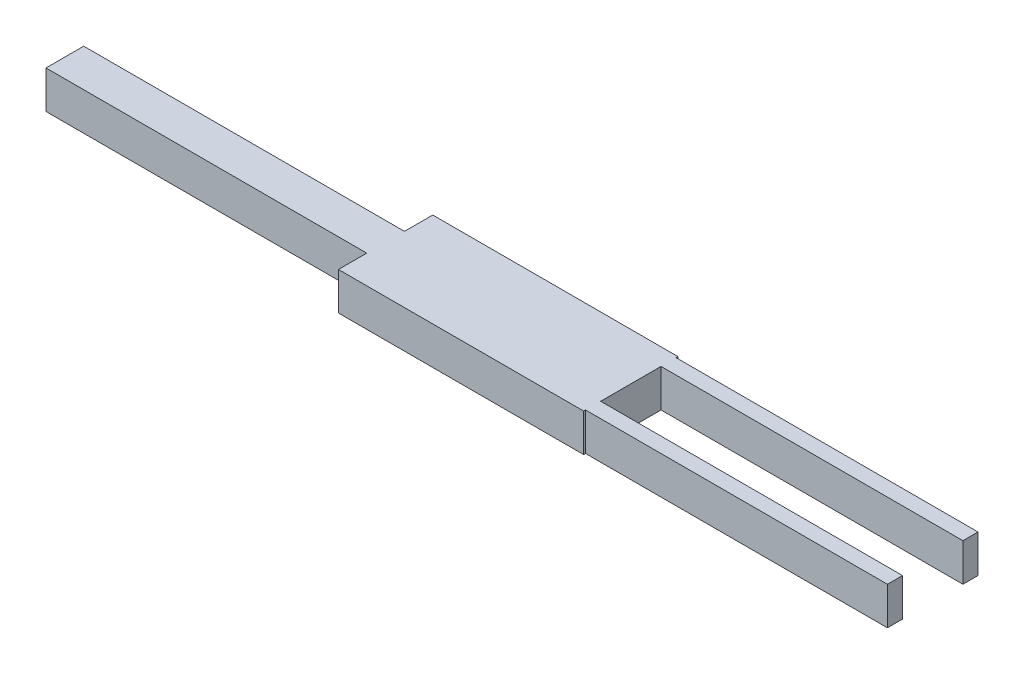
SolidWorks part; units mm, degrees
ref_plane "Front Plane" through (0, 0, 0) normal (0, 0, 1) x (1, 0, 0)
ref_plane "Top Plane" through (0, 0, 0) normal (0, 1, 0) x (1, 0, 0)
ref_plane "Right Plane" through (0, 0, 0) normal (1, 0, 0) x (0, 0, -1)
sketch "Sketch1" plane through (0, 0, 0) normal (0, 1, 0) x (1, 0, 0)
  line L0 (251.1979, 10.1864) -> (171.1979, 10.1864)
  line L1 (171.1979, 10.1864) -> (171.1979, -5.8136)
  line L2 (171.1979, -5.8136) -> (251.1979, -5.8136)
  line L3 (251.1979, 10.1864) -> (251.1979, 14.1864)
  line L12 (21.1979, -2.8136) -> (106.1979, -2.8136)
  line L16 (106.1979, -2.8136) -> (106.1979, -10.3136)
  line L17 (106.1979, -10.3136) -> (171.1979, -10.3136)
  line L18 (171.1979, -10.3136) -> (171.1979, -9.8136)
  line L19 (171.1979, -9.8136) -> (251.1979, -9.8136)
  line L20 (251.1979, -9.8136) -> (251.1979, -5.8136)
  line L21 (251.1979, 14.1864) -> (171.1979, 14.1864)
  line L22 (171.1979, 14.1864) -> (171.1979, 14.6864)
  line L23 (171.1979, 14.6864) -> (106.1979, 14.6864)
  line L24 (106.1979, 14.6864) -> (106.1979, 7.1864)
  line L25 (106.1979, 7.1864) -> (21.1979, 7.1864)
  line L26 (21.1979, 7.1864) -> (21.1979, -2.8136)
  dimension "D2" = 4
  dimension "D9" = 10
  dimension "D10" = 65
  dimension "D11" = 25
  dimension "D12" = 80
  dimension "D13" = 24
extrude "Boss-Extrude1" add sketch "Sketch1" along normal blind 10
